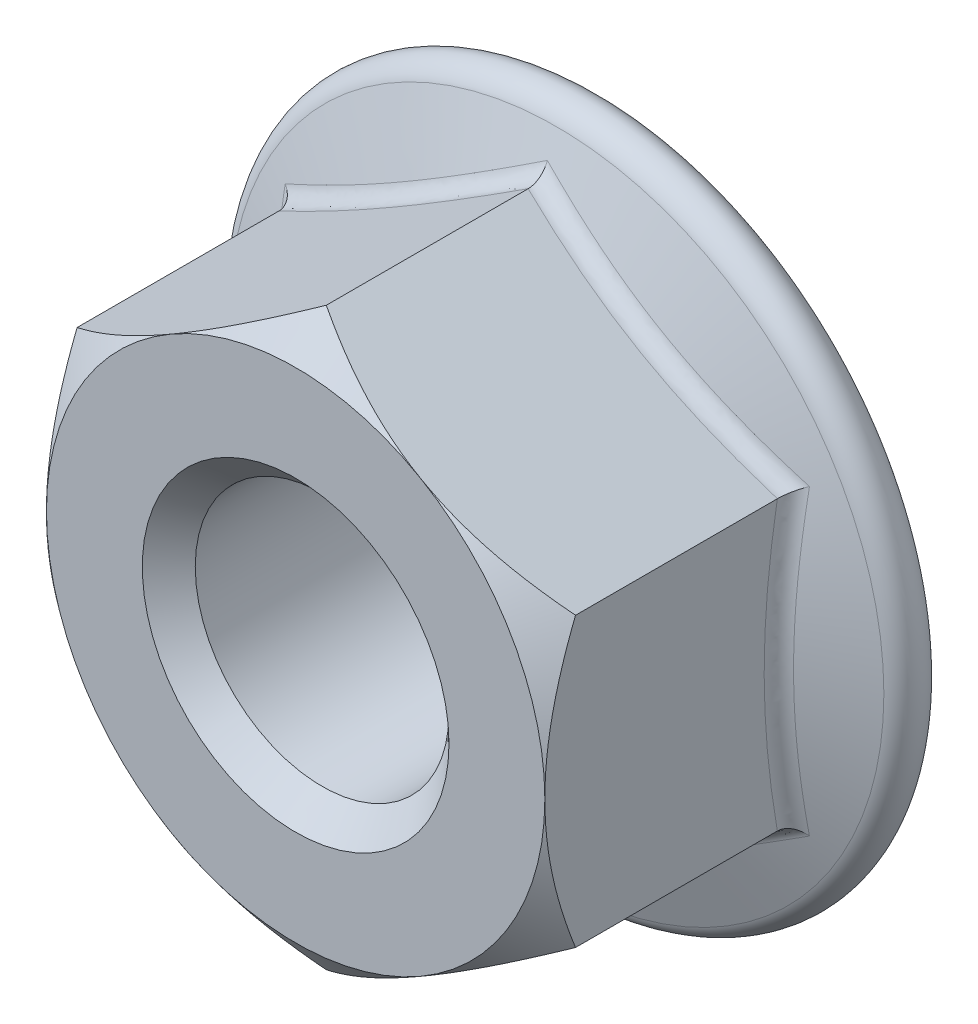
SolidWorks part; units mm, degrees
material "Acciaio al carbonio semplice"
ref_plane "Piano frontale" through (0, 0, 0) normal (0, 0, 1) x (1, 0, 0)
ref_plane "Piano superiore" through (0, 0, 0) normal (0, 1, 0) x (1, 0, 0)
ref_plane "Piano destro" through (0, 0, 0) normal (1, 0, 0) x (0, 0, -1)
sketch "Schizzo1" plane through (0, 0, 0) normal (0, 0, 1) x (1, 0, 0)
  line L1 (0, 7.5056) -> (-6.5, 3.7528)
  line L2 (-6.5, 3.7528) -> (-6.5, -3.7528)
  line L3 (-6.5, -3.7528) -> (0, -7.5056)
  line L4 (0, -7.5056) -> (6.5, -3.7528)
  line L5 (6.5, -3.7528) -> (6.5, 3.7528)
  line L6 (6.5, 3.7528) -> (0, 7.5056)
  circle A0 centre (0, 0) radius 6.5 construction
  circle A1 centre (0, 0) radius 3.3095
  dimension "D1" = 6.619
  dimension "D2" = 13
extrude "Estrusione-Estrusione1" add sketch "Schizzo1" along normal blind 8
cosmetic thread "Filettatura cosmetica2" parameters "D2"=8
ref_axis "Assi1" through (0, 0, 8) along (0, 0, -1)
sketch "Schizzo2" plane through (0, 0, 0) normal (1, 0, 0) x (0, 0, -1)
  line L0 (0, 3.3095) -> (0, 8.3313)
  line L1 (0, -3.7528) -> (0, 3.7528) construction
  line L2 (0, 3.3095) -> (-3.1048, 3.3095)
  line L3 (-3.1048, 3.3095) -> (-1.2, 8.5429)
  line L4 (0, 0) -> (-7.9984, 0) construction
  line L5 (-8, 0) -> (0, 0) construction
  line L6 (0, -3.3095) -> (-3.1048, -3.3095) construction
  line L7 (-3.1048, -3.3095) -> (-1.2, -8.5429) construction
  line L8 (0, -3.3095) -> (0, -8.3313) construction
  line L9 (-0.6187, -8.95) -> (2.1825, -8.95) construction
  line L10 (-0.6187, 8.95) -> (2.1825, 8.95) construction
  arc A0 (0, 8.3313) -> (-1.2, 8.5429) centre (-0.6187, 8.3313) ccw
  arc A1 (0, -8.3313) -> (-1.2, -8.5429) centre (-0.6187, -8.3313) cw construction
  dimension "D4" = 17.9
  dimension "D1" = 20
  dimension "D2" = 6.619
  dimension "D3" = 1.2
revolve "Rivoluzione1" add sketch "Schizzo2" angle 360 about L4
sketch "Schizzo3" plane through (0, 0, 0) normal (1, 0, 0) x (0, 0, -1)
  line L0 (-8, 6.5) -> (-7.2, 7.5056)
  line L1 (-8, 3.7528) -> (-8, 7.5056) construction
  line L2 (-8, 7.5056) -> (-1.5776, 7.5056) construction
  line L3 (-7.2, 7.5056) -> (-7.2, 20.2056)
  line L4 (-7.2, 20.2056) -> (-20.7, 20.2056)
  line L5 (-20.7, 20.2056) -> (-20.7, 6.5)
  line L6 (-20.7, 6.5) -> (-8, 6.5)
  line L7 (-4, 7.5056) -> (-4, 20.9337) construction
  line L8 (12.7, 6.5) -> (0, 6.5) construction
  line L9 (12.7, 20.2056) -> (12.7, 6.5) construction
  line L10 (-0.8, 20.2056) -> (12.7, 20.2056) construction
  line L11 (-0.8, 7.5056) -> (-0.8, 20.2056) construction
  line L12 (0, 6.5) -> (-0.8, 7.5056) construction
  line L13 (0, -8.3313) -> (0, 8.3313) construction
  dimension "D1" = 4
  dimension "D2" = 12.7
  dimension "D3" = 12.7
  dimension "D4" = 6.5
  dimension "D5" = 0.8
revolve "Taglia-Rivoluzione1" cut sketch "Schizzo3" angle 360 about axis through (0, 0, 8) along (0, 0, -1)
fillet "Raccordo1" radius 0.48 6 edges
chamfer "Smusso1" distance 0.6905 angle 45 2 edges at (3.3095, 0, 0) (3.3095, 0, 8)
